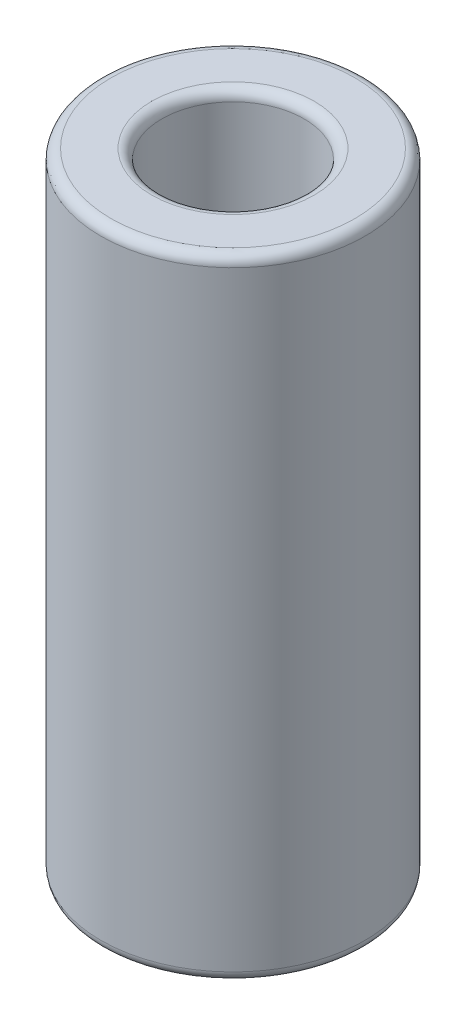
SolidWorks part; units mm, degrees
ref_plane "Front Plane" through (0, 0, 0) normal (0, 0, 1) x (1, 0, 0)
ref_plane "Top Plane" through (0, 0, 0) normal (0, 1, 0) x (1, 0, 0)
ref_plane "Right Plane" through (0, 0, 0) normal (1, 0, 0) x (0, 0, -1)
sketch "Sketch1" plane through (0, 0, 0) normal (0, 1, 0) x (1, 0, 0)
  circle A0 centre (0, 0) radius 13
  circle A1 centre (0, 0) radius 7
  dimension "D1" = 26
  dimension "D2" = 14
extrude "Boss-Extrude1" add sketch "Sketch1" along normal blind 62
fillet "Fillet2" radius 1 2 edges at (0, 0, 13) (0, 62, 13)
fillet "Fillet3" radius 1 2 edges at (0, 0, 7) (0, 62, 7)
